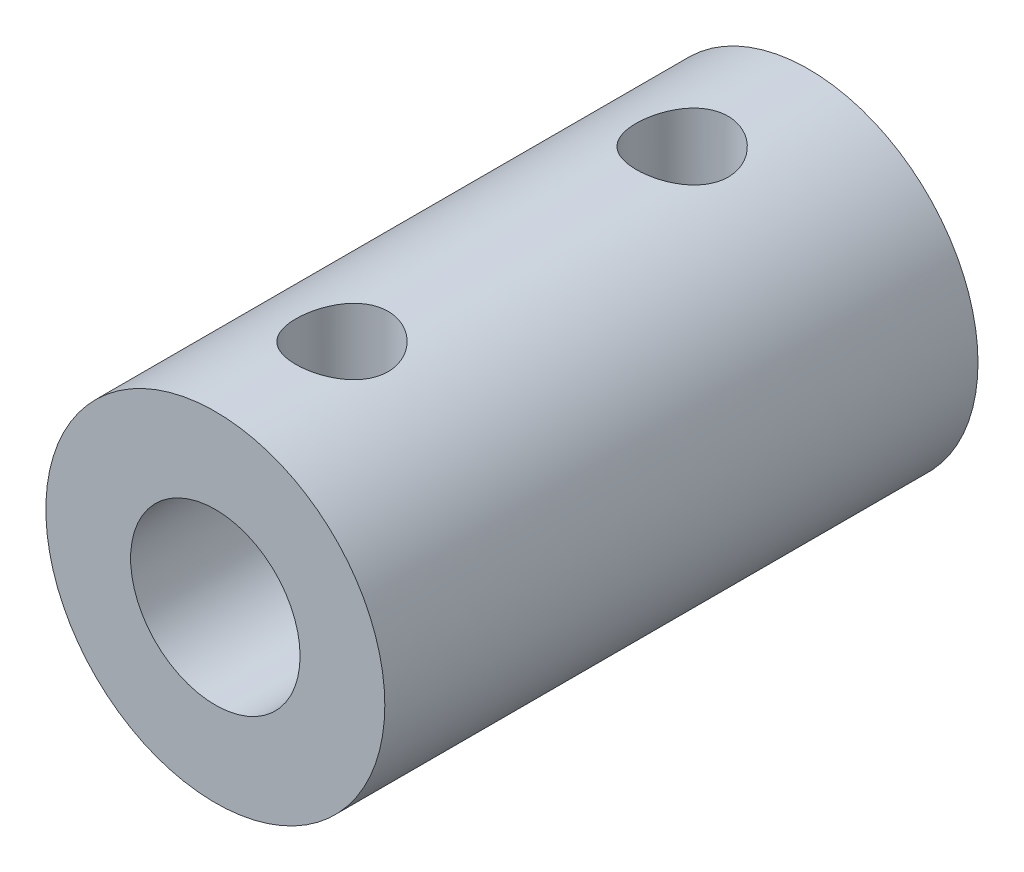
SolidWorks part; units mm, degrees
ref_plane "Front Plane" through (0, 0, 0) normal (0, 0, 1) x (1, 0, 0)
ref_plane "Top Plane" through (0, 0, 0) normal (0, 1, 0) x (1, 0, 0)
ref_plane "Right Plane" through (0, 0, 0) normal (1, 0, 0) x (0, 0, -1)
sketch "Sketch1" plane through (0, 0, 0) normal (0, 0, 1) x (1, 0, 0)
  circle A0 centre (0, 0) radius 6.35
  dimension "D1" = 12.7
extrude "Boss-Extrude1" add sketch "Sketch1" along normal blind 22.225
sketch "Sketch2" plane through (0, 0, 22.225) normal (0, 0, 1) x (1, 0, 0)
  circle A0 centre (0, 0) radius 3.175
  dimension "D1" = 6.35
extrude "Thick" cut sketch "Sketch2" against normal blind 12.7
sketch "Sketch3" plane through (0, 0, 0) normal (0, 0, -1) x (-1, 0, 0)
  circle A0 centre (0, 0) radius 2.3813
  dimension "D1" = 4.7625
extrude "Thin" cut sketch "Sketch3" against normal blind 12.7
hole_wizard "#8-32 Tapped Hole2" positions "3DSketch3" profile "Sketch11" tap size "#8-32" standard "ANSI Inch"
sketch3d "3DSketch3"
  point P0 (-0.0176, 6.35, 17.4625)
  point P2 (0.0282, 6.3499, 4.7625)
  point P6 (0, 0, 0)
  point P7 (0, 0, 0)
  point P8 (0, 0, 0)
sketch "Sketch11" plane through (-0.0176, 6.35, 17.4625) normal (0, 0, 1) x (-1, -0.0028, 0)
  line L0 (0, 0) -> (0, 3.175)
  line L1 (0, 3.175) -> (1.7272, 3.175)
  line L2 (1.7272, 3.175) -> (1.7272, 0)
  line L5 (1.7272, 0) -> (0, 0)
  line L11 (0, -6.35) -> (0, 107.95) construction
  dimension "Thru Tap Drill Dia." = 3.4544
  dimension "Thru Tap Drill Depth" = 3.175
cosmetic thread "Hole Thread4" parameters "D2"=4.1656
cosmetic thread "Hole Thread5" parameters "D2"=4.1656
